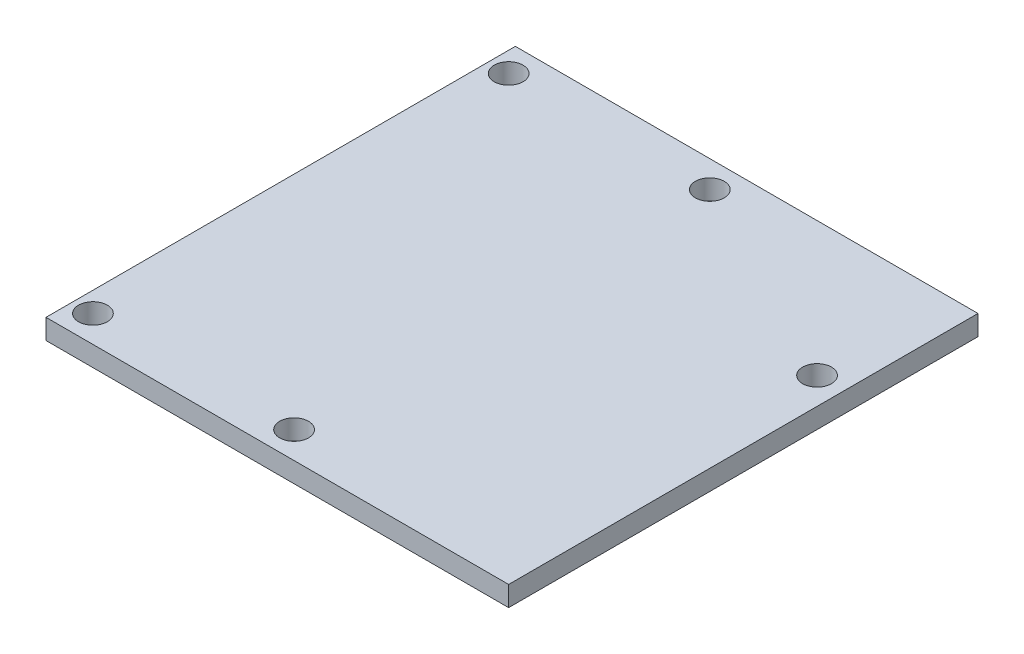
SolidWorks part; units mm, degrees
ref_plane "Front Plane" through (0, 0, 0) normal (0, 0, 1) x (1, 0, 0)
ref_plane "Top Plane" through (0, 0, 0) normal (0, 1, 0) x (1, 0, 0)
ref_plane "Right Plane" through (0, 0, 0) normal (1, 0, 0) x (0, 0, -1)
sketch "Sketch1" plane through (0, 0, 0) normal (0, 1, 0) x (1, 0, 0)
  line L0 (18, 35) -> (51, 35)
  line L1 (-15, -31) -> (15, -31) construction
  line L2 (-15, -31) -> (-15, 31) construction
  line L3 (-15, 31) -> (15, 31) construction
  line L4 (15, -31) -> (15, 31) construction
  line L5 (-15, -31) -> (15, 31) construction
  line L6 (-15, 31) -> (15, -31) construction
  line L7 (-18, -35) -> (18, -35)
  line L8 (-18, -35) -> (-18, 35)
  line L9 (-18, 35) -> (18, 35)
  line L10 (18, -35) -> (18, 35) construction
  line L11 (-18, -35) -> (18, 35) construction
  line L12 (-18, 35) -> (18, -35) construction
  line L13 (51, 35) -> (51, -35)
  line L14 (51, -35) -> (18, -35)
  circle A0 centre (15, 31) radius 2.15
  circle A1 centre (-15, 31) radius 2.15
  circle A2 centre (-15, -31) radius 2.15
  circle A3 centre (15, -31) radius 2.15
  circle A4 centre (47, 15) radius 2.15
  point P0 (0, 0)
  point P10 (0, 0)
  dimension "D2" = 4.3
  dimension "D1" = 30
  dimension "62" = 62
  dimension "D3" = 36
  dimension "D4" = 70
  dimension "D5" = 33
  dimension "D6" = 20
  dimension "D7" = 4
extrude "Boss-Extrude1" add sketch "Sketch1" along normal blind 3
